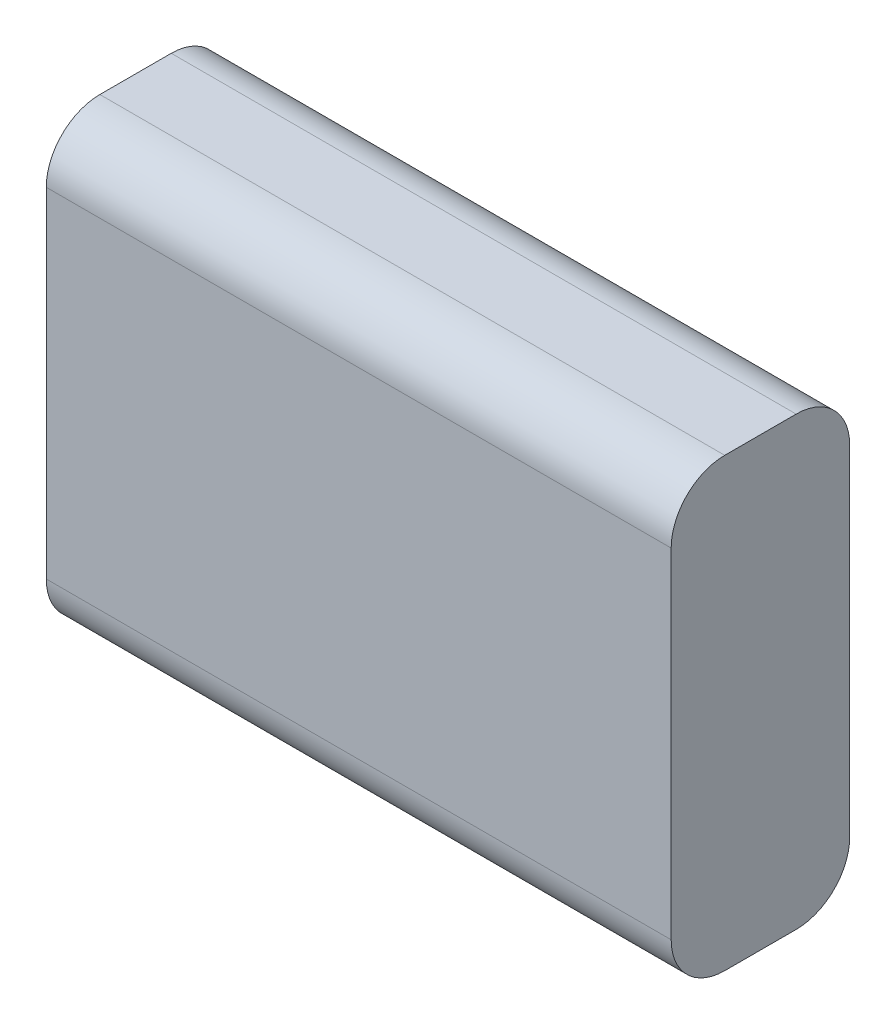
SolidWorks part; units mm, degrees
ref_plane "Front Plane" through (0, 0, 0) normal (0, 0, 1) x (1, 0, 0)
ref_plane "Top Plane" through (0, 0, 0) normal (0, 1, 0) x (1, 0, 0)
ref_plane "Right Plane" through (0, 0, 0) normal (1, 0, 0) x (0, 0, -1)
sketch "Sketch1" plane through (0, 0, 0) normal (0, 0, 1) x (1, 0, 0)
  line L1 (0, 0) -> (35, 0)
  line L2 (0, 0) -> (0, 25)
  line L3 (0, 25) -> (35, 25)
  line L4 (35, 0) -> (35, 25)
  dimension "D1" = 35
  dimension "D2" = 25
extrude "Boss-Extrude1" add sketch "Sketch1" along normal blind 10
fillet "Fillet1" radius 3 4 edges at (17.5, 0, 0) (17.5, 0, 10) (17.5, 25, 0) (17.5, 25, 10)
